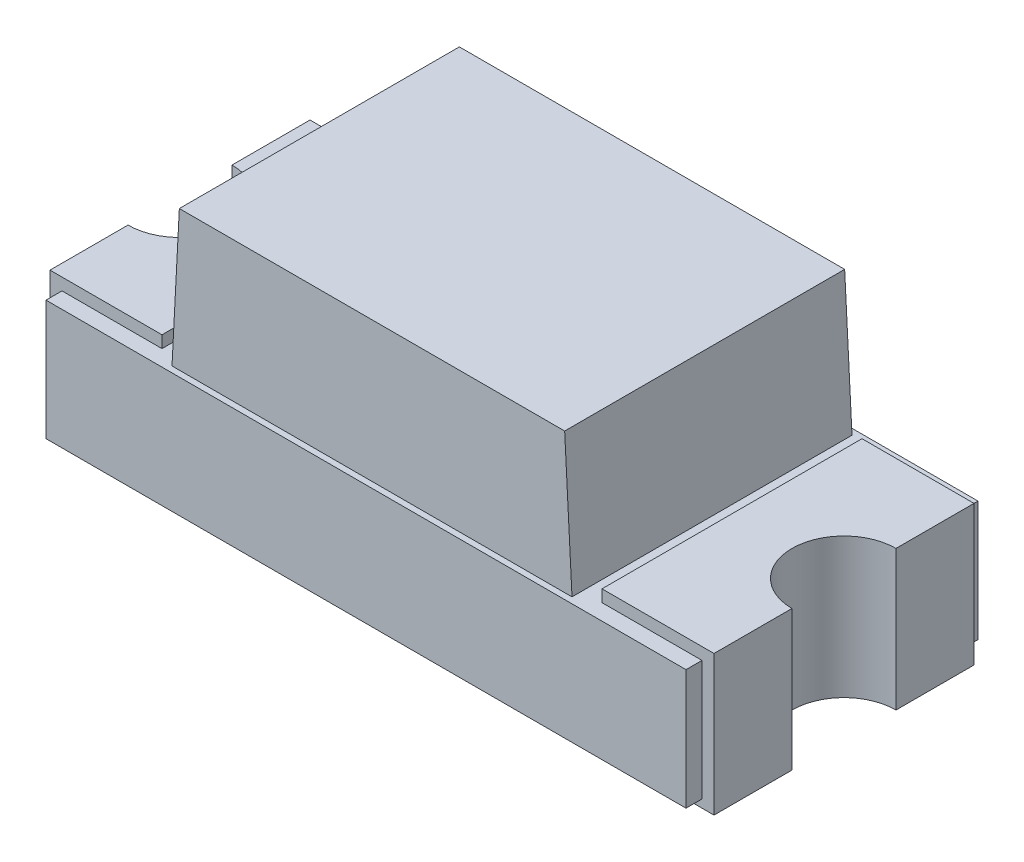
SolidWorks part; units mm, degrees
material "45"
ref_plane "前视基准面" through (0, 0, 0) normal (0, 0, 1) x (1, 0, 0)
ref_plane "上视基准面" through (0, 0, 0) normal (0, 1, 0) x (1, 0, 0)
ref_plane "右视基准面" through (0, 0, 0) normal (1, 0, 0) x (0, 0, -1)
sketch "草图1" plane through (0, 0, 0) normal (0, 1, 0) x (1, 0, 0)
  line L1 (-0.8, 0.365) -> (0.8, 0.365)
  line L2 (-0.8, 0.365) -> (-0.8, -0.365)
  line L3 (-0.8, -0.365) -> (0.8, -0.365)
  line L4 (0.8, 0.365) -> (0.8, -0.365)
  line L5 (-0.8, 0.365) -> (0.8, -0.365) construction
  line L6 (-0.8, -0.365) -> (0.8, 0.365) construction
  point P0 (0, 0)
  dimension "D1" = 1.6
  dimension "D2" = 0.73
extrude "凸台-拉伸1" add sketch "草图1" along normal mid plane 0.3
ref_plane "基准面1" through (0, 0.18, 0) normal (0, 1, 0) x (1, 0, 0)
sketch "草图2" plane through (0, 0.18, 0) normal (0, 1, 0) x (1, 0, 0)
  line L0 (-0.8, 0.365) -> (-0.8, -0.365) construction
  line L1 (-0.83, 0.325) -> (-0.55, 0.325)
  line L2 (-0.83, 0.325) -> (-0.83, -0.325)
  line L3 (-0.83, -0.325) -> (-0.55, -0.325)
  line L4 (-0.55, 0.325) -> (-0.55, -0.325)
  dimension "D1" = 0.28
  dimension "D2" = 0.65
  dimension "D3" = 0.325
  dimension "D4" = 0.03
extrude "凸台-拉伸2" add sketch "草图2" against normal blind 0.35
sketch "草图4" plane through (0, 0, 0) normal (0, 1, 0) x (1, 0, 0)
  line L0 (-0.83, 0.325) -> (-0.83, -0.325) construction
  circle A0 centre (-0.83, 0) radius 0.13
  dimension "D1" = 0.26
extrude "切除-拉伸1" cut sketch "草图4" against normal mid plane 1
mirror "镜向1" about plane through (0, 0, 0) normal (1, 0, 0) of "切除-拉伸1", "凸台-拉伸2"
sketch "草图5" plane through (0, 0.15, 0) normal (0, 1, 0) x (1, 0, 0)
  line L1 (0.5, -0.35) -> (-0.5, -0.35)
  line L2 (0.5, -0.35) -> (0.5, 0.35)
  line L3 (0.5, 0.35) -> (-0.5, 0.35)
  line L4 (-0.5, -0.35) -> (-0.5, 0.35)
  line L5 (0.5, -0.35) -> (-0.5, 0.35) construction
  line L6 (0.5, 0.35) -> (-0.5, -0.35) construction
  point P0 (0, 0)
  dimension "D1" = 1
  dimension "D2" = 0.7
extrude "凸台-拉伸3" add sketch "草图5" along normal blind 0.35
draft "拔模1" type of draft neutral plane draft angle 3 faces to draft 2 face at (0.5, 0.325, 0) face at (-0.5, 0.325, 0) neutral plane through (0, 0.15, 0) neutral plane normal (0, 1, 0) parameters "D1"=3
